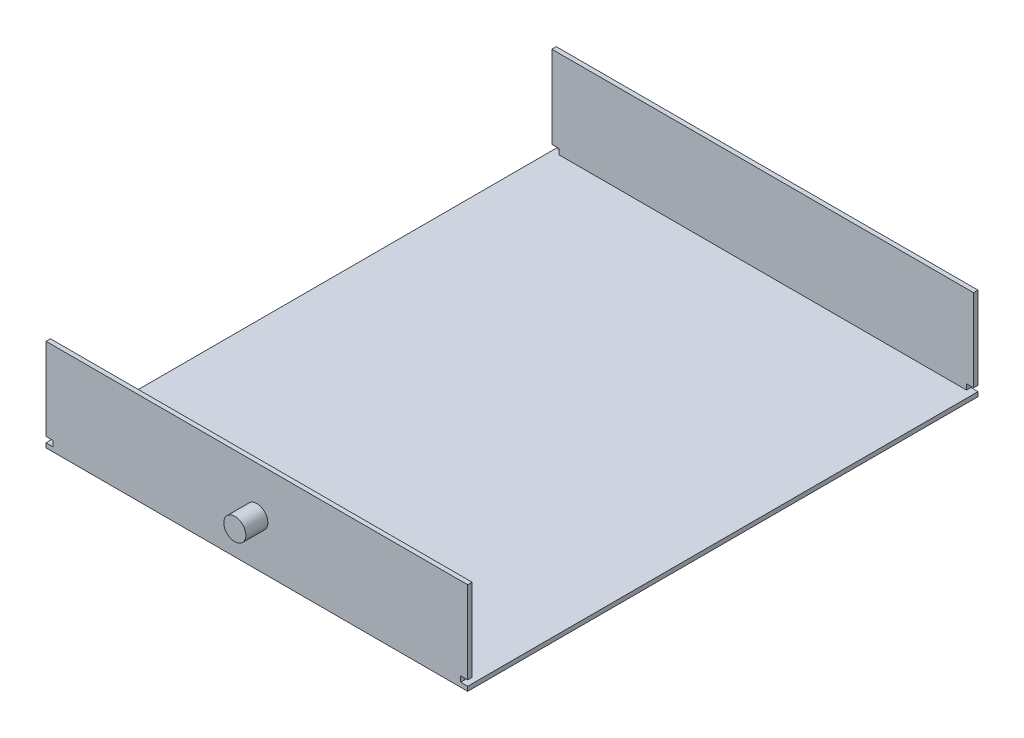
SolidWorks part; units mm, degrees
ref_plane "Front Plane" through (0, 0, 0) normal (0, 0, 1) x (1, 0, 0)
ref_plane "Top Plane" through (0, 0, 0) normal (0, 1, 0) x (1, 0, 0)
ref_plane "Right Plane" through (0, 0, 0) normal (1, 0, 0) x (0, 0, -1)
sketch "草图2" plane through (0, 0, 0) normal (0, 1, 0) x (1, 0, 0)
  line L1 (95.7, -115.8) -> (-95.7, -115.8)
  line L2 (95.7, -115.8) -> (95.7, 115.8)
  line L3 (95.7, 115.8) -> (-95.7, 115.8)
  line L4 (-95.7, -115.8) -> (-95.7, 115.8)
  line L5 (95.7, -115.8) -> (-95.7, 115.8) construction
  line L6 (95.7, 115.8) -> (-95.7, -115.8) construction
  point P0 (0, 0)
  dimension "D1" = 231.6
  dimension "D2" = 191.4
extrude "凸台-拉伸1" add sketch "草图2" along normal blind 2
sketch "草图3" plane through (0, 2, 0) normal (0, 1, 0) x (1, 0, 0)
  line L0 (95.7, 115.8) -> (-95.7, 115.8) construction
  line L1 (-92.5, 115.8) -> (92.5, 115.8)
  line L2 (-92.5, 115.8) -> (-92.5, 113.8)
  line L3 (-92.5, 113.8) -> (92.5, 113.8)
  line L4 (92.5, 115.8) -> (92.5, 113.8)
  line L5 (-95.7, 115.8) -> (-95.7, -115.8) construction
  line L6 (95.7, -115.8) -> (95.7, 115.8) construction
  line L8 (-92.5, -113.8) -> (92.5, -113.8)
  line L9 (92.5, -115.8) -> (92.5, -113.8)
  line L10 (-92.5, -115.8) -> (92.5, -115.8)
  line L11 (-92.5, -115.8) -> (-92.5, -113.8)
  dimension "D1" = 3.2
  dimension "D2" = 3.2
  dimension "D3" = 2
extrude "凸台-拉伸2" add sketch "草图3" along normal blind 2.5
sketch "草图4" plane through (0, 4.5, 0) normal (0, 1, 0) x (1, 0, 0)
  line L0 (92.5, 115.8) -> (-92.5, 115.8) construction
  line L1 (-95.7, 115.8) -> (95.7, 115.8)
  line L2 (-95.7, 115.8) -> (-95.7, 113.8)
  line L3 (-95.7, 113.8) -> (95.7, 113.8)
  line L4 (95.7, 115.8) -> (95.7, 113.8)
  line L5 (-92.5, 113.8) -> (92.5, 113.8) construction
  line L7 (95.7, -115.8) -> (95.7, 115.8) construction
  line L9 (-95.7, -113.8) -> (95.7, -113.8)
  line L10 (95.7, -115.8) -> (95.7, -113.8)
  line L11 (-95.7, -115.8) -> (95.7, -115.8)
  line L12 (-95.7, -115.8) -> (-95.7, -113.8)
  point P8 (0, 0)
extrude "凸台-拉伸3" add sketch "草图4" along normal blind 37.4
sketch "草图7" plane through (0, 0, 115.8) normal (0, 0, 1) x (1, 0, 0)
  circle A0 centre (0, 20.95) radius 5
  dimension "D1" = 10
extrude "凸台-拉伸5" add sketch "草图7" along normal blind 10
